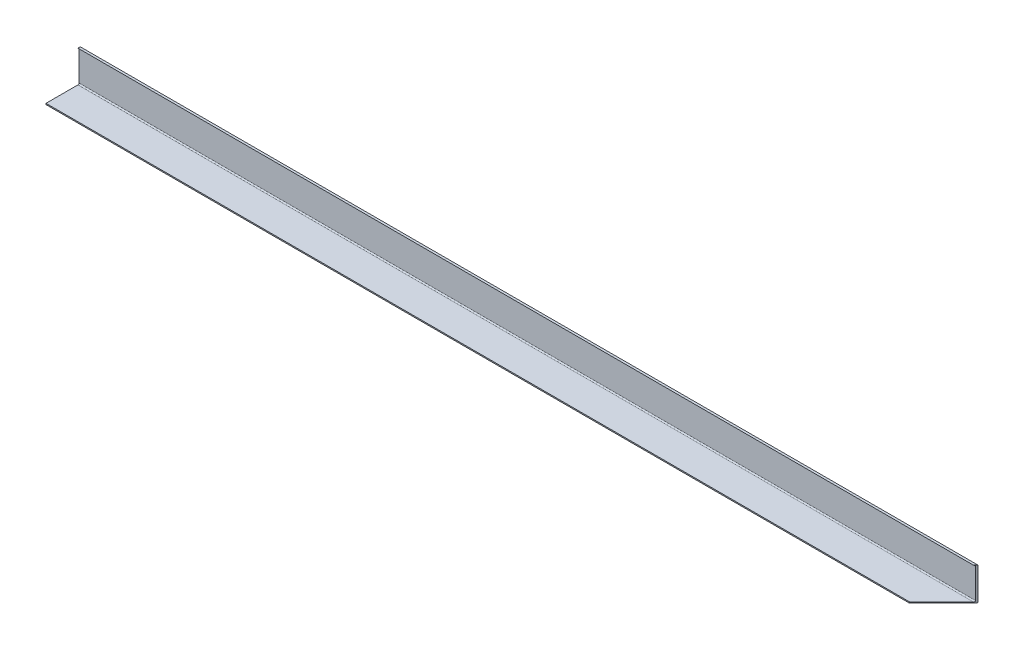
SolidWorks part; units mm, degrees
ref_plane "Front Plane" through (0, 0, 0) normal (0, 0, 1) x (1, 0, 0)
ref_plane "Top Plane" through (0, 0, 0) normal (0, 1, 0) x (1, 0, 0)
ref_plane "Right Plane" through (0, 0, 0) normal (1, 0, 0) x (0, 0, -1)
sketch "Sketch1" plane through (0, 0, 0) normal (1, 0, 0) x (0, 0, -1)
  line L0 (0, 0) -> (85, 0)
  line L1 (85, 0) -> (85, 82)
  line L2 (85, 82) -> (47, 82)
  line L3 (47, 82) -> (47, 112)
  line L4 (0, -3) -> (88, -3)
  line L5 (88, -3) -> (88, 85)
  line L6 (88, 85) -> (50, 85)
  line L7 (50, 85) -> (50, 112)
  line L8 (47, 112) -> (50, 112)
  line L9 (0, 0) -> (0, -3)
  point P11 (48.5, 112)
  dimension "D1" = 3
  dimension "D2" = 27
  dimension "D3" = 38
  dimension "D4" = 88
  dimension "D5" = 88
extrude "Boss-Extrude1" add sketch "Sketch1" along normal blind 2310
fillet "Fillet1" radius 3 6 edges at (1155, -3, -88) (1155, 85, -88) (1155, 85, -50) (1155, 82, -85) (1155, 0, -85) (1155, 82, -47)
sketch "Sketch3" plane through (0, 0, 0) normal (0, 1, 0) x (1, 0, 0)
  line L0 (2310, 88) -> (2222, 0)
  line L1 (2310, 0) -> (0, 0) construction
  line L2 (2222, 0) -> (2310, 0)
  line L3 (2310, 0) -> (2310, 88)
  dimension "D1" = 45
extrude "Cut-Extrude1" cut sketch "Sketch3" along normal blind 85 and the other way through all
sketch "Sketch6" plane through (0, 0, -47) normal (0, 0, 1) x (1, 0, 0)
  line L0 (2310, 112) -> (0, 112)
  line L1 (2310, 112) -> (0, 112) construction
  line L2 (0, 112) -> (0, 82)
  line L3 (0, 82) -> (2304, 82) construction
  line L4 (0, 82) -> (2310, 82)
  line L5 (2310, 82) -> (2310, 112)
  dimension "D1" = 2310
extrude "Cut-Extrude2" cut sketch "Sketch6" against normal blind 41
equation "\"D1@Boss-Extrude1\"= \"indoorHeight\" + \"indoorHeight_para\" + 80 + \"rearLightHeight_para\""
equation "\"CarBeamWidth\"=700.0"
equation "\"WheelWidth\"=650.0"
equation "\"Wheel_FrontBoxDistance\"=1390.0"
equation "\"boxLength\"=5100.0"
equation "\"boxWidth\"=1930.0"
equation "\"MetalSheet_3mm_length\"=5030.0"
equation "\"MetalSheet_3mm_width\"=1923.0"
equation "\"MetalSheet_3mm_FloorCut_L_length\"=1764.0"
equation "\"MetalSheet_3mm_FloorCut_L_disdance\"=1665.0"
equation "\"MetalSheet_3mm_FloorCut_R_length\"=1764.0"
equation "\"MetalSheet_3mm_FloorCut_R_disdance\"=1665.0"
equation "\"indoorHeight\"=1940.0"
equation "\"indoorHeight_para\"=25.0"
equation "\"rearLightHeight_para\"=265.0"
equation "\"haveDoor_R\"=1"
equation "\"side_door_bottom_R_3mm_length\"=1934.0"
equation "\"side_door_bottom_R_3mm_toFrontDistance\"=1583.0"
equation "\"1Bar_Side_RF_3mm_length\"=1493.0"
equation "\"1Bar_Side_RB_3mm_length\"=1493.0"
equation "\"DoorSeparator_RF_3mm_withHinge_toFrontDistance\"=1673.0"
equation "\"DoorSeparator_RF_3mm_withHinge_exist\"=1"
equation "\"DoorSeparator_RB_3mm_withHinge_toFrontDistance\"=3427.0"
equation "\"DoorSeparator_RB_3mm_withHinge_exist\"=1"
equation "\"Door_R1_L_open_Single_toFrontDistance\"=2547.5"
equation "\"Door_R1_L_open_Single_exist\"=1"
equation "\"door_base_long7_R1_L_open_Single_height\"=1890.0"
equation "\"door_base_short7_R1_L_open_Single_height\"=1890.0"
equation "\"door_base_short7_R1_L_open_Single_width\"=864"
equation "\"Door_R1_R_open_Single_toFrontDistance\"=3422.0"
equation "\"Door_R1_R_open_Single_exist\"=1"
equation "\"door_base_long7_R1_R_open_Single_height\"=1890.0"
equation "\"door_base_short7_R1_R_open_Single_height\"=1890.0"
equation "\"door_base_short7_R1_R_open_Single_width\"=864"
equation "\"x\"=66.0"
equation "\"door_base_double_BL_height\"=1890.0"
equation "\"door_base_short7_BL_Single_height\"=1890.0"
equation "\"door_base_short7_BL_Single_width\"=864"
equation "\"door_base_long7_BR_Single_height\"=1890.0"
equation "\"door_base_short7_BR_Single_height\"=1890.0"
equation "\"door_base_short7_BR_Single_width\"=864"
equation "\"da\"=62.0"
equation "\"SquareTube_length\"=1923.0"
equation "\"channelSteel_length\"=5030.0"
equation "\"SquareTube_inFront_AvgDistance\"=285.0"
equation "\"SquareTube_inFront_TotalCount\"=5"
equation "\"SquareTube_inFront1_cutDepth50_R\"=0.5"
equation "\"SquareTube_inFront1_cutDepth50_L\"=0.5"
equation "\"SquareTube_inFront2_cutDepth50_R\"=0.5"
equation "\"SquareTube_inFront2_cutDepth50_L\"=0.5"
equation "\"SquareTube_inFront3_cutDepth50_R\"=0.5"
equation "\"SquareTube_inFront3_cutDepth50_L\"=0.5"
equation "\"SquareTube_inFront4_cutDepth50_R\"=0.5"
equation "\"SquareTube_inFront4_cutDepth50_L\"=0.5"
equation "\"SquareTube_inFront5_cutDepth50_R\"=50"
equation "\"SquareTube_inFront5_cutDepth50_L\"=50"
equation "\"SquareTube_inFront6_cutDepth50_R\"=50"
equation "\"SquareTube_inFront6_cutDepth50_L\"=50"
equation "\"SquareTube_inFront7_cutDepth50_R\"=50"
equation "\"SquareTube_inFront7_cutDepth50_L\"=50"
equation "\"SquareTube_inFront8_cutDepth50_R\"=50"
equation "\"SquareTube_inFront8_cutDepth50_L\"=50"
equation "\"SquareTube_inFront9_cutDepth50_R\"=50"
equation "\"SquareTube_inFront9_cutDepth50_L\"=50"
equation "\"SquareTube_inFront10_cutDepth50_R\"=50"
equation "\"SquareTube_inFront10_cutDepth50_L\"=50"
equation "\"SquareTube_inFront11_cutDepth50_R\"=50"
equation "\"SquareTube_inFront11_cutDepth50_L\"=50"
equation "\"SquareTube_inFront12_cutDepth50_R\"=50"
equation "\"SquareTube_inFront12_cutDepth50_L\"=50"
equation "\"SquareTube_inFront13_cutDepth50_R\"=50"
equation "\"SquareTube_inFront13_cutDepth50_L\"=50"
equation "\"SquareTube_inFront14_cutDepth50_R\"=50"
equation "\"SquareTube_inFront14_cutDepth50_L\"=50"
equation "\"SquareTube_inBack_AvgDistance\"=333.125"
equation "\"SquareTube_inBack_TotalCount\"=9"
equation "\"SquareTube_inBack1_cutDepth50_R\"=50"
equation "\"SquareTube_inBack1_cutDepth50_L\"=50"
equation "\"SquareTube_inBack2_cutDepth50_R\"=50"
equation "\"SquareTube_inBack2_cutDepth50_L\"=50"
equation "\"SquareTube_inBack3_cutDepth50_R\"=50"
equation "\"SquareTube_inBack3_cutDepth50_L\"=50"
equation "\"SquareTube_inBack4_cutDepth50_R\"=50"
equation "\"SquareTube_inBack4_cutDepth50_L\"=50"
equation "\"SquareTube_inBack5_cutDepth50_R\"=50"
equation "\"SquareTube_inBack5_cutDepth50_L\"=50"
equation "\"SquareTube_inBack6_cutDepth50_R\"=0.5"
equation "\"SquareTube_inBack6_cutDepth50_L\"=0.5"
equation "\"SquareTube_inBack7_cutDepth50_R\"=0.5"
equation "\"SquareTube_inBack7_cutDepth50_L\"=0.5"
equation "\"SquareTube_inBack8_cutDepth50_R\"=0.5"
equation "\"SquareTube_inBack8_cutDepth50_L\"=0.5"
equation "\"doorColumnBar_A_FR_3mm_length_Cut\"=2310.0"
equation "\"A\"=0.0"
equation "\"doorColumnBar_A_FL_3mm_length_Cut\"=2310.0"
equation "\"D1@Sketch6\"=\"doorColumnBar_A_FL_3mm_length_Cut\""
equation "\"B\"=0.0"
equation "\"haveDoor_L\"=1"
equation "\"side_door_bottom_L_3mm_length\"=1934.0"
equation "\"side_door_bottom_L_3mm_toFrontDistance\"=1583.0"
equation "\"1Bar_Side_LF_3mm_length\"=1493.0"
equation "\"1Bar_Side_LB_3mm_length\"=1493.0"
equation "\"DoorSeparator_LF_3mm_withHinge_toFrontDistance\"=1673.0"
equation "\"DoorSeparator_LF_3mm_withHinge_exist\"=1"
equation "\"DoorSeparator_LB_3mm_withHinge_toFrontDistance\"=3427.0"
equation "\"DoorSeparator_LB_3mm_withHinge_exist\"=1"
equation "\"Door_L1_L_open_Single_toFrontDistance\"=3422.0"
equation "\"Door_L1_L_open_Single_exist\"=1"
equation "\"door_base_long7_L1_L_open_Single_height\"=1890.0"
equation "\"door_base_short7_L1_L_open_Single_height\"=1890.0"
equation "\"door_base_short7_L1_L_open_Single_width\"=864"
equation "\"Door_L1_R_open_Single_toFrontDistance\"=2547.5"
equation "\"Door_L1_R_open_Single_exist\"=1"
equation "\"door_base_long7_L1_R_open_Single_height\"=1890.0"
equation "\"door_base_short7_L1_R_open_Single_height\"=1890.0"
equation "\"door_base_short7_L1_R_open_Single_width\"=864"
